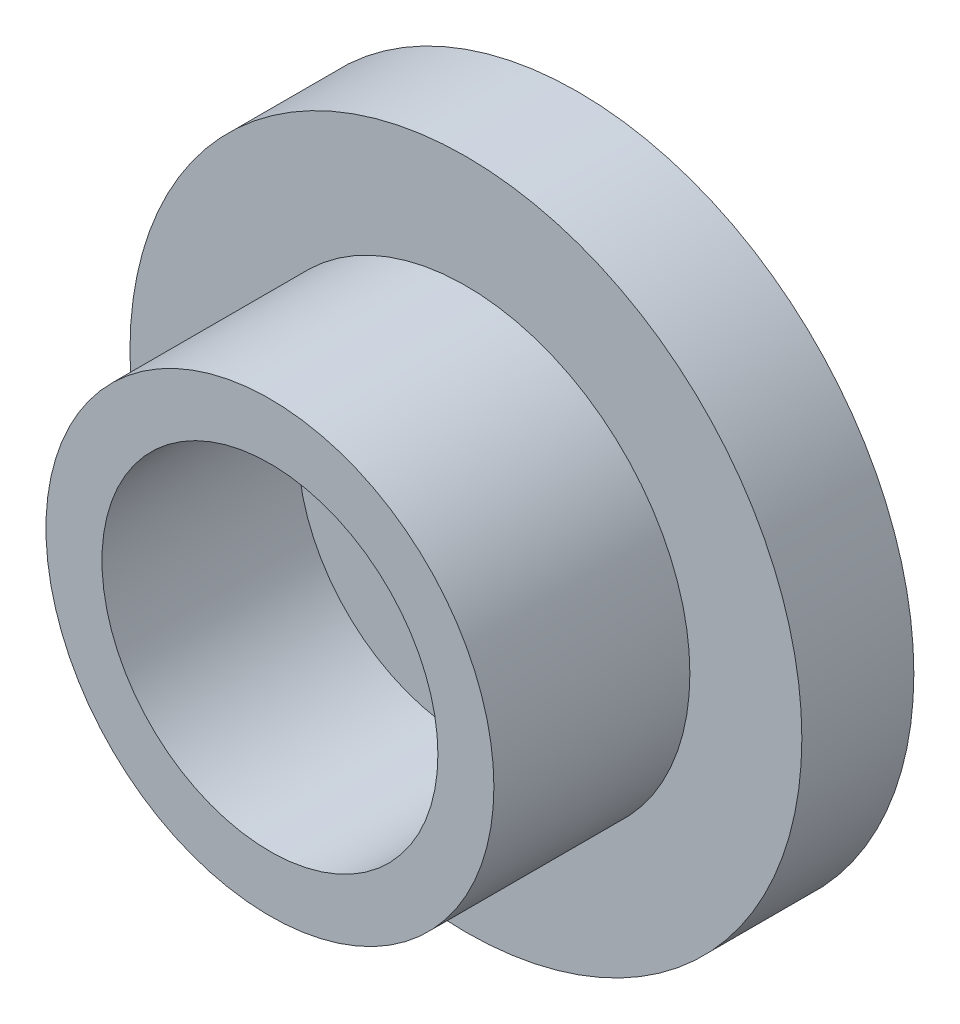
SolidWorks part; units mm, degrees
ref_plane "Front Plane" through (0, 0, 0) normal (0, 0, 1) x (1, 0, 0)
ref_plane "Top Plane" through (0, 0, 0) normal (0, 1, 0) x (1, 0, 0)
ref_plane "Right Plane" through (0, 0, 0) normal (1, 0, 0) x (0, 0, -1)
sketch "Sketch1" plane through (0, 0, 0) normal (0, 0, 1) x (1, 0, 0)
  circle A0 centre (0, 0) radius 6
  dimension "D1" = 12
extrude "Boss-Extrude1" add sketch "Sketch1" along normal blind 2
sketch "Sketch2" plane through (0, 0, 2) normal (0, 0, 1) x (1, 0, 0)
  circle A0 centre (0, 0) radius 3
  circle A1 centre (0, 0) radius 4
  dimension "D1" = 6
  dimension "D2" = 8
extrude "Boss-Extrude2" add sketch "Sketch2" along normal blind 3.5
